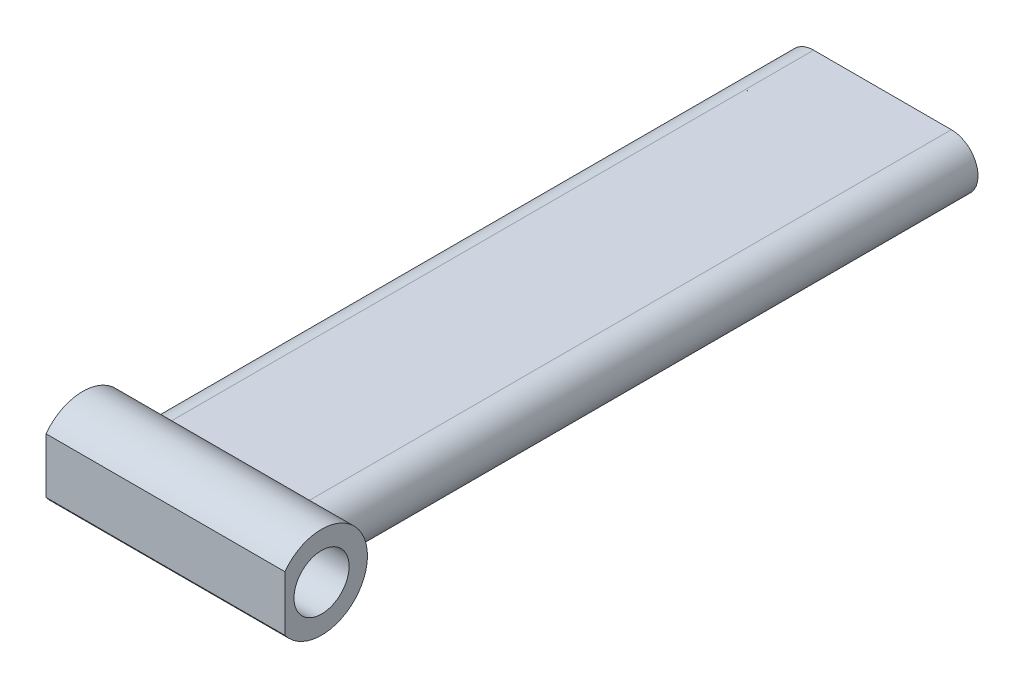
SolidWorks part; units mm, degrees
ref_plane "Front Plane" through (0, 0, 0) normal (0, 0, 1) x (1, 0, 0)
ref_plane "Top Plane" through (0, 0, 0) normal (0, 1, 0) x (1, 0, 0)
ref_plane "Right Plane" through (0, 0, 0) normal (1, 0, 0) x (0, 0, -1)
sketch "Sketch2" plane through (0, 0, 0) normal (0, 0, 1) x (1, 0, 0)
  line L0 (7.5, 0) -> (-7.5, 0) construction
  line L1 (7.5, -2.9) -> (-7.5, -2.9)
  line L2 (7.5, 2.9) -> (-7.5, 2.9)
  arc A0 (7.5, -2.9) -> (7.5, 2.9) centre (7.5, 0) ccw
  arc A1 (-7.5, 2.9) -> (-7.5, -2.9) centre (-7.5, 0) ccw
  point P2 (0, 0)
  dimension "D2" = 2.9
  dimension "D1" = 15
sketch "Sketch4" plane through (0, 0, 0) normal (0, 0, 1) x (1, 0, 0)
  line L0 (7.5, 0) -> (-7.5, 0) construction
  line L1 (7.5, -2.9) -> (-7.5, -2.9)
  line L2 (7.5, 2.9) -> (-7.5, 2.9)
  line L3 (7.5, -1.9) -> (-7.5, -1.9)
  line L4 (7.5, 1.9) -> (-7.5, 1.9)
  arc A0 (7.5, -2.9) -> (7.5, 2.9) centre (7.5, 0) ccw
  arc A1 (-7.5, 2.9) -> (-7.5, -2.9) centre (-7.5, 0) ccw
  arc A2 (-7.5, 1.9) -> (-7.5, -1.9) centre (-7.5, 0) ccw
  arc A3 (7.5, -1.9) -> (7.5, 1.9) centre (7.5, 0) ccw
  point P2 (0, 0)
  dimension "D2" = 2.9
  dimension "D3" = 1
  dimension "D1" = 15
extrude "Boss-Extrude1" add sketch "Sketch4" along normal mid plane 70
ref_plane "Plane1" through (7.5, 2.9, 35) normal (-1, 0, 0) x (0, 0, 1)
ref_plane "Plane2" through (-7.5, 2.9, -35) normal (-1, 0, 0) x (0, 0, 1)
sketch "Sketch9" plane through (0, 0, 0) normal (1, 0, 0) x (0, 0, -1)
  line L0 (-35, 2.9) -> (-35, -2.9) construction
  line L2 (-35, 2.9153) -> (-35, -2.8847) construction
  circle A0 centre (-39.0731, 0.0153) radius 5
  circle A1 centre (-39.0731, 0.0153) radius 3
  dimension "D1" = 10
  dimension "D2" = 6
extrude "Boss-Extrude3" add sketch "Sketch9" along normal mid plane 26 contours A0
sketch "Sketch10" plane through (0, 0, 0) normal (0, 1, 0) x (1, 0, 0)
  line L1 (-22.062, -43.0731) -> (17.6828, -43.0731)
  line L2 (-22.062, -43.0731) -> (-22.062, -50.023)
  line L3 (-22.062, -50.023) -> (17.6828, -50.023)
  line L4 (17.6828, -43.0731) -> (17.6828, -50.023)
  line L6 (-13, -44.0731) -> (13, -44.0731) construction
  dimension "D1" = 1
extrude "Cut-Extrude1" cut sketch "Sketch10" against normal mid plane 26
sketch "Sketch12" plane through (13, 0, 0) normal (1, 0, 0) x (0, 0, -1)
  circle A0 centre (-39.0731, 0.0153) radius 3
  dimension "D1" = 6
extrude "Cut-Extrude3" cut sketch "Sketch12" against normal through all
